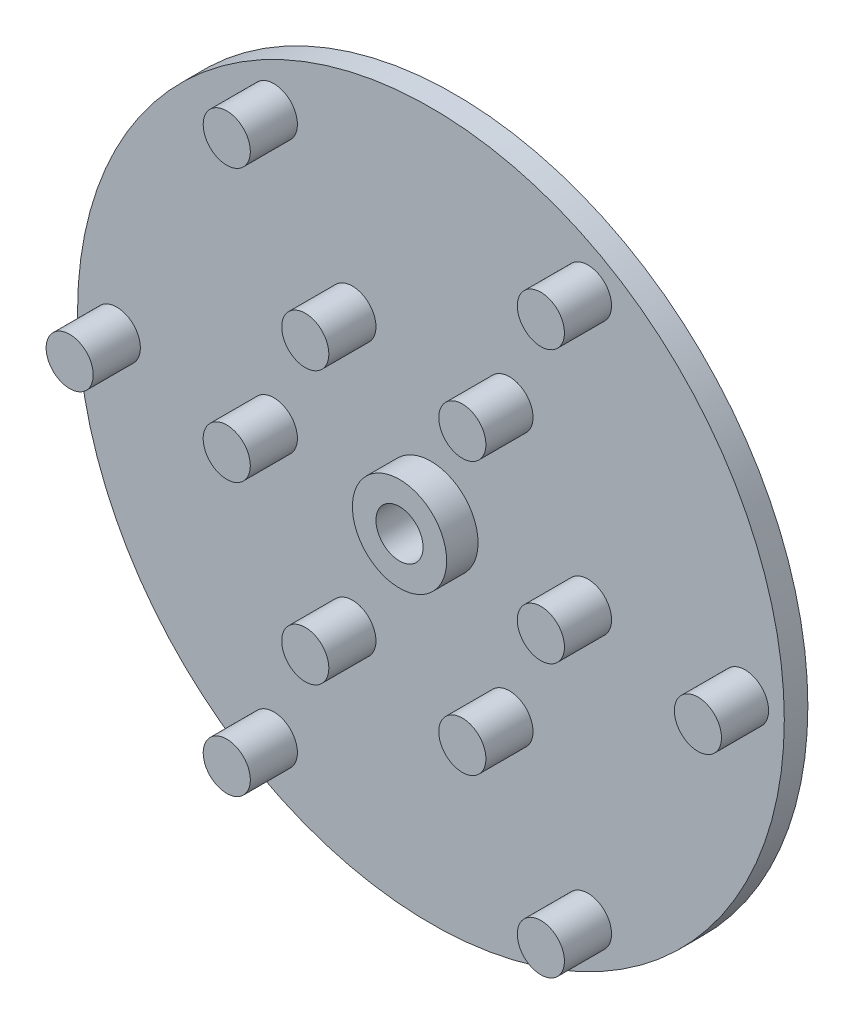
SolidWorks part; units mm, degrees
ref_plane "前视基准面" through (0, 0, 0) normal (0, 0, 1) x (1, 0, 0)
ref_plane "上视基准面" through (0, 0, 0) normal (0, 1, 0) x (1, 0, 0)
ref_plane "右视基准面" through (0, 0, 0) normal (1, 0, 0) x (0, 0, -1)
other "Configuration Table"
sketch "草图1" plane through (0, 0, 0) normal (0, 0, 1) x (1, 0, 0)
  circle A0 centre (0, 0) radius 45
  point P0 (0, 0)
  point P1 (0, 0)
  point P19 (0, 0)
  dimension "D1" = 90
extrude "凸台-拉伸1" add sketch "草图1" against normal blind 3 contours A0
sketch "草图2" plane through (0, 0, 0) normal (0, 0, 1) x (1, 0, 0)
  line L0 (0, 0) -> (-40, 0) construction
  circle A0 centre (0, 0) radius 3
  circle A1 centre (-40, 0) radius 3
  circle A2 centre (-20, 34.641) radius 3
  circle A3 centre (20, 34.641) radius 3
  circle A4 centre (40, 0) radius 3
  circle A5 centre (20, -34.641) radius 3
  circle A6 centre (-20, -34.641) radius 3
  point P17 (0, 0)
  dimension "D1" = 6
  dimension "D2" = 40
  dimension "D3" = 6
extrude "凸台-拉伸2" add sketch "草图2" along normal blind 6
sketch "草图3" plane through (0, 0, 0) normal (0, 0, 1) x (1, 0, 0)
  circle A0 centre (0, 0) radius 6
  dimension "D1" = 12
extrude "凸台-拉伸3" add sketch "草图3" along normal blind 4 and the other way blind 5
sketch "草图4" plane through (0, 0, 4) normal (0, 0, 1) x (1, 0, 0)
  circle A0 centre (0, 0) radius 3
  dimension "D1" = 6
extrude "切除-拉伸1" cut sketch "草图4" against normal up to next
sketch "草图5" plane through (0, 0, 0) normal (0, 0, 1) x (1, 0, 0)
  line L0 (0, 0) -> (-40, 0) construction
  circle A0 centre (-20, 0) radius 3
  circle A1 centre (-10, 17.3205) radius 3
  circle A2 centre (10, 17.3205) radius 3
  circle A3 centre (20, 0) radius 3
  circle A4 centre (10, -17.3205) radius 3
  circle A5 centre (-10, -17.3205) radius 3
  point P7 (-8.6519, 15.8941)
  point P8 (0, 0)
  point P18 (0, 0)
  dimension "D1" = 6
  dimension "D2" = 20
  dimension "D3" = 6
extrude "凸台-拉伸4" add sketch "草图5" along normal blind 6
